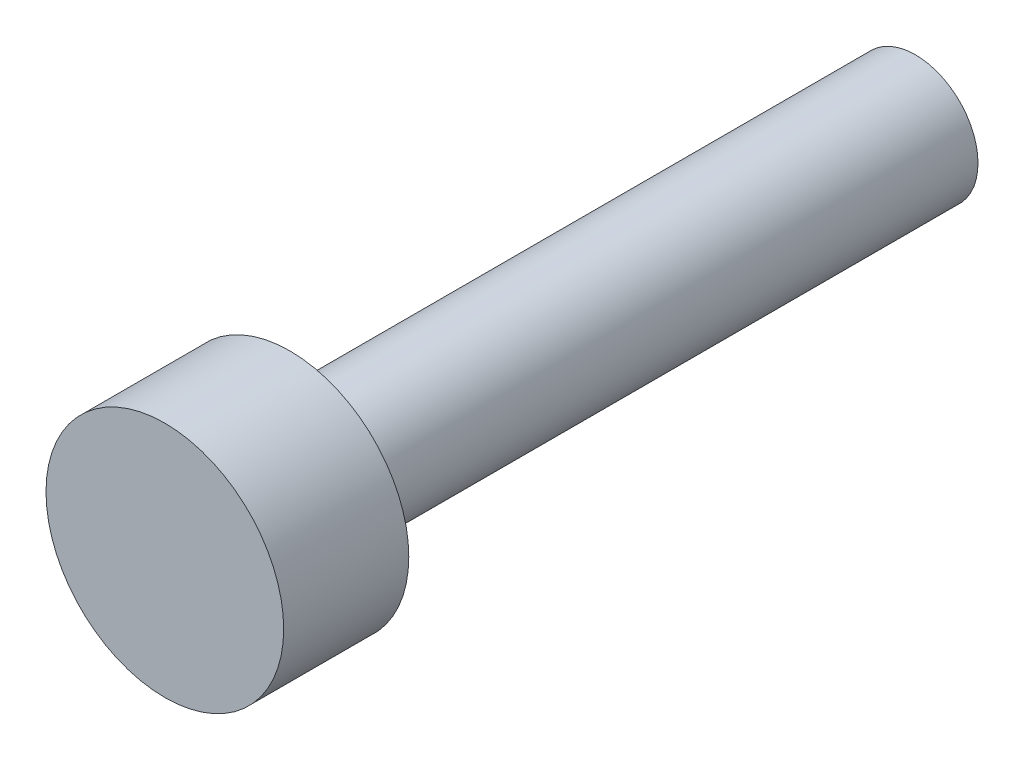
SolidWorks part; units mm, degrees
ref_plane "Front Plane" through (0, 0, 0) normal (0, 0, 1) x (1, 0, 0)
ref_plane "Top Plane" through (0, 0, 0) normal (0, 1, 0) x (1, 0, 0)
ref_plane "Right Plane" through (0, 0, 0) normal (1, 0, 0) x (0, 0, -1)
sketch "Sketch1" plane through (0, 0, 0) normal (0, 0, 1) x (1, 0, 0)
  circle A0 centre (0, 0) radius 1
extrude "Thread_Envelope" add sketch "Sketch1" along normal blind 10 from offset 10
sketch "Sketch2" plane through (0, 0, 0) normal (0, 0, 1) x (1, 0, 0)
  circle A0 centre (0, 0) radius 1.9
extrude "Head_Envelope" add sketch "Sketch2" along normal blind 2
